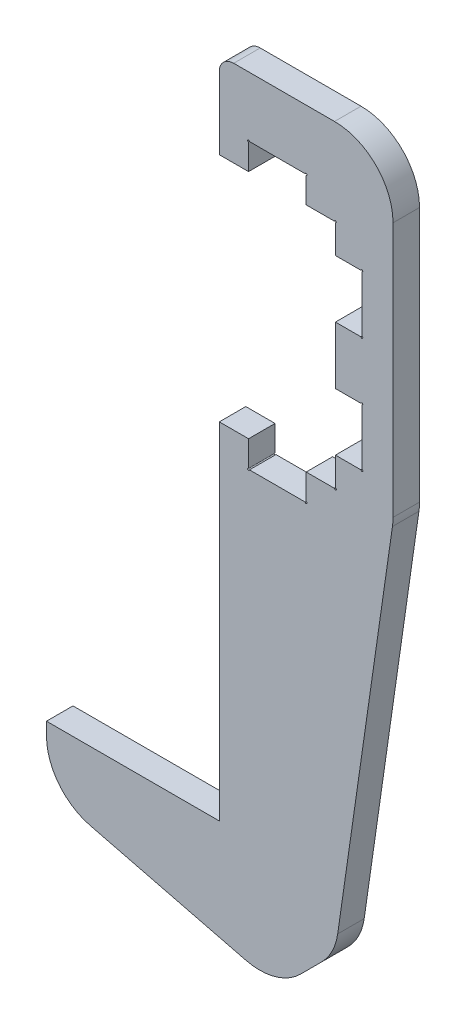
SolidWorks part; units mm, degrees
ref_plane "Front Plane" through (0, 0, 0) normal (0, 0, 1) x (1, 0, 0)
ref_plane "Top Plane" through (0, 0, 0) normal (0, 1, 0) x (1, 0, 0)
ref_plane "Right Plane" through (0, 0, 0) normal (1, 0, 0) x (0, 0, -1)
sketch "Sketch1" plane through (0, 0, 0) normal (0, 0, 1) x (1, 0, 0)
  line L0 (12.8, 0) -> (-12.8, 0) construction
  line L1 (-12.8, -25.5) -> (-6.35, -25.5)
  line L2 (-12.8, 44.55) -> (12.6, 44.55)
  line L3 (-12.8, 25.5) -> (-6.35, 25.5)
  line L4 (12.8, -25.5) -> (12.8, -19.05)
  line L5 (-12.8, -25.5) -> (12.8, 25.5) construction
  line L6 (-12.8, 25.5) -> (12.8, -25.5) construction
  line L7 (0, -25.5) -> (0, 25.5) construction
  line L8 (-12.8, -25.5) -> (-12.8, -101.7)
  line L9 (-12.8, -101.7) -> (-50.9, -101.7)
  line L10 (-50.9, -101.7) -> (-50.9, -114.4)
  line L11 (-50.9, -114.4) -> (0, -127.1)
  line L12 (0, -127.1) -> (12.7, -114.4)
  line L13 (12.8, -25.5) -> (25.5, -25.5) construction
  line L14 (0, -25.5) -> (0, -127.1) construction
  line L15 (12.8, -6.35) -> (12.8, 6.35)
  line L16 (18.642, -19.05) -> (12.8, -19.05)
  line L17 (18.642, -19.05) -> (18.642, -6.35)
  line L18 (18.642, -6.35) -> (12.8, -6.35)
  line L19 (18.642, 6.35) -> (12.8, 6.35)
  line L20 (18.642, -19.05) -> (12.8, -6.35) construction
  line L21 (18.642, -6.35) -> (12.8, -19.05) construction
  line L22 (18.642, 19.05) -> (18.642, 6.35)
  line L23 (18.642, 19.05) -> (12.8, 19.05)
  line L24 (12.8, 19.05) -> (12.8, 25.5)
  line L25 (6.35, -25.5) -> (12.8, -25.5)
  line L26 (6.35, -31.342) -> (-6.35, -31.342)
  line L27 (6.35, -31.342) -> (6.35, -25.5)
  line L28 (6.35, 31.342) -> (6.35, 25.5)
  line L29 (-6.35, -31.342) -> (-6.35, -25.5)
  line L30 (6.35, -31.342) -> (-6.35, -25.5) construction
  line L31 (6.35, -25.5) -> (-6.35, -31.342) construction
  line L32 (-6.35, 31.342) -> (-6.35, 25.5)
  line L33 (6.35, 31.342) -> (-6.35, 31.342)
  line L34 (6.35, 25.5) -> (12.8, 25.5)
  line L35 (25.5, -25.5) -> (12.7, -114.4)
  line L36 (25.5, -25.5) -> (25.5, 25.3)
  line L37 (25.5, 25.3) -> (25.5, 31.65)
  line L38 (-12.8, 25.5) -> (-12.8, 44.55)
  arc A0 (12.6, 44.55) -> (25.5, 31.65) centre (12.6, 31.65) cw
  point P0 (0, 0)
  point P10 (15.721, -12.7)
  point P25 (0, -28.421)
  dimension "D1" = 25.6
  dimension "D2" = 51
  dimension "D3" = 76.2
  dimension "D4" = 38.1
  dimension "D5" = 12.7
  dimension "D6" = 25.4
  dimension "D7" = 12.7
  dimension "D8" = 12.7
  dimension "D9" = 12.7
  dimension "D10" = 5.842
  dimension "D11" = 12.7
  dimension "D12" = 12.7
  dimension "D13" = 12.7
  dimension "D14" = 5.842
  dimension "D15" = 19.05
  dimension "D16" = 25.4
  dimension "D17" = 6.35
extrude "Boss-Extrude1" add sketch "Sketch1" along normal blind 5.842
fillet "Fillet1" radius 12.7 4 edges at (25.5, -25.5, 2.921) (12.7, -114.4, 2.921) (0, -127.1, 2.921) (-50.9, -114.4, 2.921)
fillet "Fillet2" radius 3.175 1 edges at (-12.8, 44.55, 2.921)
sketch "Sketch2" plane through (0, 0, 5.842) normal (0, 0, 1) x (1, 0, 0)
  line L0 (12.8, 0) -> (0, 0) construction
  line L1 (12.8, 6.35) -> (12.8, -6.35) construction
  circle A0 centre (-6.35, 31.342) radius 0.1984
  circle A1 centre (6.35, 31.342) radius 0.1984
  circle A2 centre (18.642, 19.05) radius 0.1984
  circle A3 centre (12.8, 25.5) radius 0.1984
  circle A4 centre (18.642, 6.35) radius 0.1984
  circle A5 centre (18.642, -6.35) radius 0.1984
  circle A6 centre (12.8, -25.5) radius 0.1984
  circle A7 centre (18.642, -19.05) radius 0.1984
  circle A8 centre (6.35, -31.342) radius 0.1984
  circle A9 centre (-6.35, -31.342) radius 0.1984
  dimension "D1" = 0.3969
  dimension "D2" = 0.3969
  dimension "D3" = 0.3969
  dimension "D4" = 0.3969
  dimension "D5" = 0.3969
extrude "Cut-Extrude1" cut sketch "Sketch2" against normal through all
